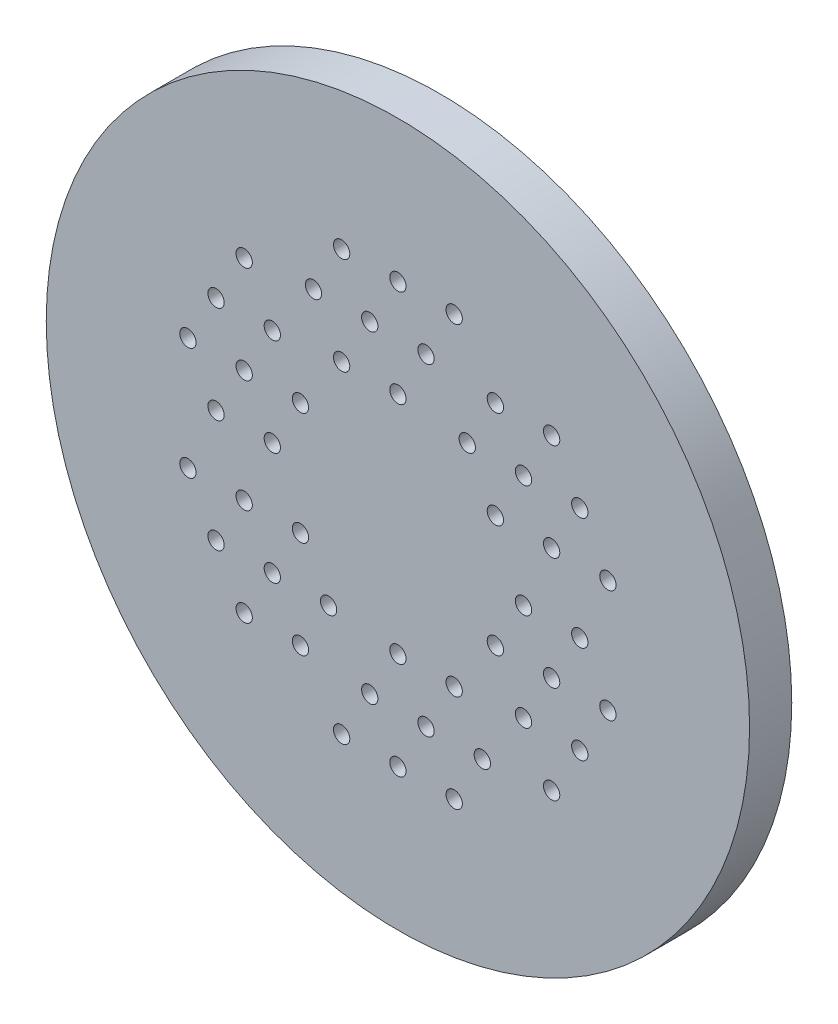
SolidWorks part; units mm, degrees
ref_plane "Front Plane" through (0, 0, 0) normal (0, 0, 1) x (1, 0, 0)
ref_plane "Top Plane" through (0, 0, 0) normal (0, 1, 0) x (1, 0, 0)
ref_plane "Right Plane" through (0, 0, 0) normal (1, 0, 0) x (0, 0, -1)
sketch "Sketch1" plane through (0, 0, 0) normal (0, 0, 1) x (1, 0, 0)
  circle A0 centre (0, 0) radius 76.2
  dimension "Top Injector Diameter" = 152.4
extrude "Boss-Extrude1" add sketch "Sketch1" along normal blind 3.81
sketch "Sketch2" plane through (0, 0, 0) normal (0, 0, -1) x (-1, 0, 0)
  line L0 (0, 0) -> (0, 10.16) construction
  line L1 (0, 10.16) -> (5.08, 10.16) construction
  line L2 (5.08, 10.16) -> (7.62, 14.5594) construction
  line L3 (7.62, 14.5594) -> (2.54, 14.5594) construction
  line L4 (2.54, 14.5594) -> (5.08, 10.16) construction
  line L5 (0, 10.16) -> (2.54, 14.5594) construction
  line L6 (0, 10.16) -> (-2.54, 14.5594) construction
  line L7 (-2.54, 14.5594) -> (2.54, 14.5594) construction
  line L8 (2.54, 14.5594) -> (5.08, 18.9588) construction
  line L9 (5.08, 18.9588) -> (7.62, 14.5594) construction
  line L10 (-2.54, 14.5594) -> (-5.08, 18.9588) construction
  line L11 (-5.08, 18.9588) -> (0, 18.9588) construction
  line L12 (0, 18.9588) -> (-2.54, 14.5594) construction
  line L13 (0, 18.9588) -> (2.54, 14.5594) construction
  line L14 (0, 18.9588) -> (5.08, 18.9588) construction
  circle A0 centre (0, 10.16) radius 0.7366
  circle A1 centre (2.54, 14.5594) radius 0.7366
  circle A2 centre (5.08, 10.16) radius 0.7366
  circle A3 centre (7.62, 14.5594) radius 0.7366
  circle A4 centre (-2.54, 14.5594) radius 0.7366
  circle A5 centre (-5.08, 18.9588) radius 0.7366
  circle A6 centre (0, 18.9588) radius 0.7366
  circle A7 centre (5.08, 18.9588) radius 0.7366
  dimension "Top Injector Hole Diameter" = 1.4732
  dimension "Distance Between Holes" = 5.08
  dimension "Top Injector Hole Distance from Center" = 10.16
extrude "Cut-Extrude1" cut sketch "Sketch2" against normal through all
pattern_circular "CirPattern1" count 6 over 360 about axis through (0, 0, 0) along (0, 0, 1) of "Cut-Extrude1"
sketch "Sketch3" plane through (0, 0, 0) normal (0, 0, -1) x (-1, 0, 0)
  line L0 (-41.275, 0) -> (41.275, 0) construction
  circle A0 centre (41.275, 0) radius 6.35
  circle A1 centre (-41.275, 0) radius 6.35
  point P4 (0, 0)
  dimension "Top Injector Valves Diameter" = 12.7
  dimension "Top Injector Manifold Valves" = 82.55
extrude "Cut-Extrude2" cut sketch "Sketch3" against normal through all
sketch "Sketch5" plane through (0, 0, 0) normal (0, 0, -1) x (-1, 0, 0)
  line L0 (0, 0) -> (66.802, 0) construction
  circle A0 centre (66.802, 0) radius 3.175
  dimension "Top Injector Hole Diameter" = 6.35
  dimension "Top Injector Screw Holes Distance" = 66.802
extrude "Cut-Extrude3" cut sketch "Sketch5" against normal through all
pattern_circular "CirPattern2" count 8 over 360 about axis through (0, 0, 0) along (0, 0, 1) of "Cut-Extrude3"
sketch "Sketch6" plane through (0, 0, 0) normal (1, 0, 0) x (0, 0, -1)
  line L0 (0, -76.2) -> (0, 76.2) construction
  line L1 (0, 53.34) -> (1.27, 53.34)
  line L2 (0, 53.34) -> (0, 50.8)
  line L3 (0, 50.8) -> (1.27, 50.8)
  line L4 (1.27, 53.34) -> (1.27, 50.8)
  line L5 (0, 76.2) -> (-3.81, 76.2) construction
  line L6 (0, 0) -> (-3.81, 0) construction
  line L7 (-3.81, 76.2) -> (-3.81, -76.2) construction
  dimension "Locator Ring Width" = 2.54
  dimension "Locator Ring Distance From Edge" = 25.4
  dimension "Locator Ring Depth" = 1.27
revolve "Revolve1" add sketch "Sketch6" angle 360 about L6
sketch "Sketch7" plane through (0, 0, 0) normal (0, 0, 1) x (1, 0, 0)
  circle A0 centre (0, 0) radius 31.75
  circle A1 centre (0, 0) radius 76.2
extrude "Cut-Extrude4" cut sketch "Sketch7" along normal through all both and the other way through all
equation "\"Top Injector Diameter\"=6"
equation "\"Top Injector Height\"=0.15"
equation "\"Distance Between Holes\"=0.2"
equation "\"Top Injector Hole Distance from Center\"=0.4"
equation "\"Top Injector Hole Diameter\"=0.058"
equation "\"Top Injector Manifold Valves\"=3.25"
equation "\"Top Injector Valves Diameter\"=0.5"
equation "\"Top Injector Screw Holes Distance\"=2.63"
equation "\"Top Injector Screw Hole Diameter\"=0.25"
